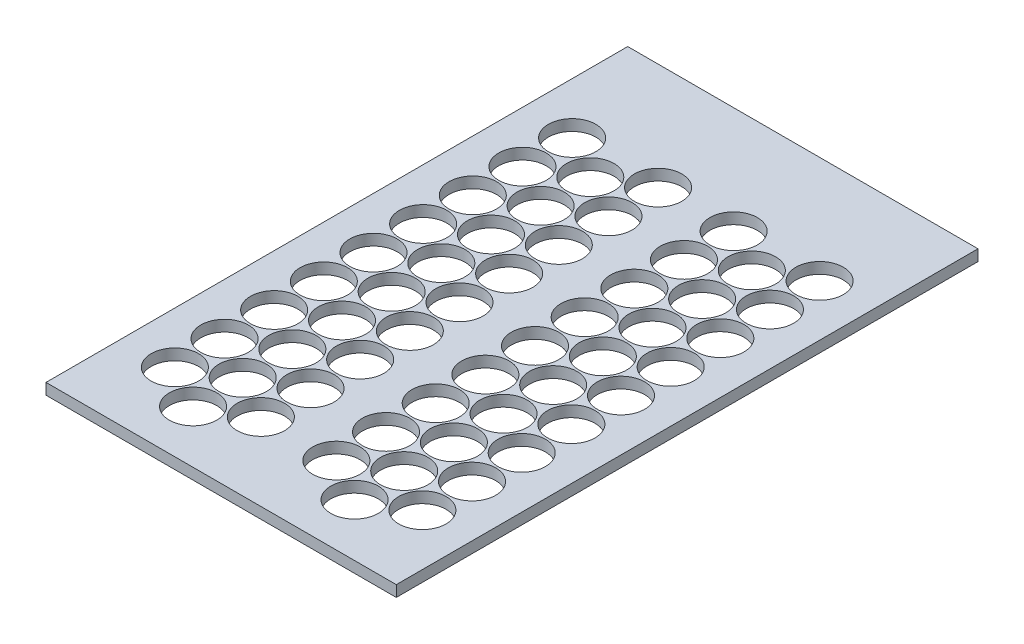
SolidWorks part; units mm, degrees
ref_plane "Front Plane" through (0, 0, 0) normal (0, 0, 1) x (1, 0, 0)
ref_plane "Top Plane" through (0, 0, 0) normal (0, 1, 0) x (1, 0, 0)
ref_plane "Right Plane" through (0, 0, 0) normal (1, 0, 0) x (0, 0, -1)
sketch "Sketch1" plane through (0, 0, 0) normal (0, 1, 0) x (1, 0, 0)
  line L0 (-40.2913, 121.2683) -> (-20.6524, 109.9298) construction
  line L1 (-63.7663, 170.1433) -> (96.2432, 170.1433)
  line L2 (-63.7663, 170.1433) -> (-63.7663, -95.5882)
  line L3 (-63.7663, -95.5882) -> (96.2432, -95.5882)
  line L4 (96.2432, 170.1433) -> (96.2432, -95.5882)
  line L5 (-63.7663, 170.1433) -> (96.2432, -95.5882) construction
  line L6 (-63.7663, -95.5882) -> (96.2432, 170.1433) construction
  line L7 (-20.6524, 109.9298) -> (-40.2913, 109.9298) construction
  line L8 (-40.2913, 109.9298) -> (-40.2913, 121.2683) construction
  line L9 (-20.6524, 109.9298) -> (-1.0135, 121.2683) construction
  line L10 (-1.0135, 121.2683) -> (-1.0135, 109.9298) construction
  line L11 (-1.0135, 109.9298) -> (-20.6524, 109.9298) construction
  line L12 (16.2385, 170.1433) -> (16.2385, -95.5882) construction
  line L13 (-63.7663, 37.2776) -> (96.2432, 37.2776) construction
  line L14 (-40.2913, 121.2683) -> (-40.2913, 98.5861) construction
  circle A0 centre (-40.2913, 121.2683) radius 10.8385
  circle A1 centre (-20.6524, 109.9298) radius 10.8385
  circle A2 centre (-1.0135, 121.2683) radius 10.8385
  circle A3 centre (-40.2913, 98.5861) radius 10.8385
  circle A4 centre (-20.6524, 87.2476) radius 10.8385
  circle A5 centre (-1.0135, 98.5861) radius 10.8385
  circle A6 centre (-40.2913, 75.9039) radius 10.8385
  circle A7 centre (-20.6524, 64.5654) radius 10.8385
  circle A8 centre (-1.0135, 75.9039) radius 10.8385
  circle A9 centre (-40.2913, 53.2217) radius 10.8385
  circle A10 centre (-20.6524, 41.8832) radius 10.8385
  circle A11 centre (-1.0135, 53.2217) radius 10.8385
  circle A12 centre (-40.2913, 30.5395) radius 10.8385
  circle A13 centre (-20.6524, 19.201) radius 10.8385
  circle A14 centre (-1.0135, 30.5395) radius 10.8385
  circle A15 centre (-40.2913, 7.8573) radius 10.8385
  circle A16 centre (-20.6524, -3.4812) radius 10.8385
  circle A17 centre (-1.0135, 7.8573) radius 10.8385
  circle A18 centre (-40.2913, -14.8249) radius 10.8385
  circle A19 centre (-20.6524, -26.1634) radius 10.8385
  circle A20 centre (-1.0135, -14.8249) radius 10.8385
  circle A21 centre (-40.2913, -37.5071) radius 10.8385
  circle A22 centre (-20.6524, -48.8456) radius 10.8385
  circle A23 centre (-1.0135, -37.5071) radius 10.8385
  circle A24 centre (-40.2913, -60.1893) radius 10.8385
  circle A25 centre (-20.6524, -71.5278) radius 10.8385
  circle A26 centre (-1.0135, -60.1893) radius 10.8385
  circle A27 centre (72.7682, 7.8573) radius 10.8385
  circle A28 centre (53.1293, 19.201) radius 10.8385
  circle A29 centre (33.4905, 7.8573) radius 10.8385
  circle A30 centre (53.1293, -3.4812) radius 10.8385
  circle A31 centre (72.7682, -14.8249) radius 10.8385
  circle A32 centre (33.4905, -14.8249) radius 10.8385
  circle A33 centre (53.1293, -26.1634) radius 10.8385
  circle A34 centre (33.4905, -37.5071) radius 10.8385
  circle A35 centre (72.7682, -37.5071) radius 10.8385
  circle A36 centre (72.7682, -60.1893) radius 10.8385
  circle A37 centre (53.1293, -48.8456) radius 10.8385
  circle A38 centre (33.4905, -60.1893) radius 10.8385
  circle A39 centre (53.1293, -71.5278) radius 10.8385
  circle A40 centre (72.7682, 30.5395) radius 10.8385
  circle A41 centre (33.4905, 30.5395) radius 10.8385
  circle A42 centre (53.1293, 41.8832) radius 10.8385
  circle A43 centre (72.7682, 53.2217) radius 10.8385
  circle A44 centre (33.4905, 53.2217) radius 10.8385
  circle A45 centre (53.1293, 64.5654) radius 10.8385
  circle A46 centre (72.7682, 75.9039) radius 10.8385
  circle A47 centre (33.4905, 75.9039) radius 10.8385
  circle A48 centre (53.1293, 87.2476) radius 10.8385
  circle A49 centre (72.7682, 98.5861) radius 10.8385
  circle A50 centre (53.1293, 109.9298) radius 10.8385
  circle A51 centre (33.4905, 98.5861) radius 10.8385
  circle A52 centre (33.4905, 121.2683) radius 10.8385
  circle A53 centre (72.7682, 121.2683) radius 10.8385
  point P0 (0, 0)
  dimension "D1" = 21.677
  dimension "D2" = 22.677
  dimension "D3" = 30
  dimension "D4" = 23.475
  dimension "D5" = 48.875
  dimension "D6" = 160.0094
  dimension "D7" = 265.7315
  dimension "D9" = 22.6822
  dimension "D8" = 9
extrude "Boss-Extrude1" add sketch "Sketch1" along normal blind 5.08
equation "\"CellHole\"= \"CellDia\" + \"PocketTolerance\""
equation "\"D1@Sketch1\"=\"CellHole\""
equation "\"CellGap\"= 1mm"
equation "\"CellAngle\"= 30"
equation "\"D2@Sketch1\"=\"CellHole\"+\"CellGap\""
equation "\"SenseSpace\"= .5"
equation "\"SideBorder\"= .5"
equation "\"ParallelWidth\"= \"CellHole\" + cos ( \"CellAngle\" ) * 2 * ( \"CellHole\" + \"CellGap\" )"
equation "\"CellRad\"= \"CellDia\" / 2"
equation "\"D4@Sketch1\"=\"CellRad\"+\"SideBorder\""
equation "\"TopBorder\" = 1.5in"
equation "\"BottomBorder\"= .5in"
equation "\"D5@Sketch1\"=\"CellRad\"+\"TopBorder\""
equation "\"D6@Sketch1\"=2*(\"SideBorder\" + \"ParallelWidth\") + \"SenseSpace\""
equation "\"SeriesLength\"= \"NumSeries\" * ( \"CellHole\" + \"CellGap\" ) + \"HoleRad\""
equation "\"NumSeries\"= 9"
equation "\"ParallelLength\"= \"CellRad\" + sin ( \"CellAngle\" ) * ( \"CellHole\" + \"CellGap\" )"
equation "\"D7@Sketch1\"=\"TopBorder\" + \"SeriesLength\" + \"BottomBorder\""
equation "\"PocketTolerance\"= .005in"
equation "\"CellDia\"= 21.55mm"
equation "\"HoleRad\"= \"CellHole\" / 2"
